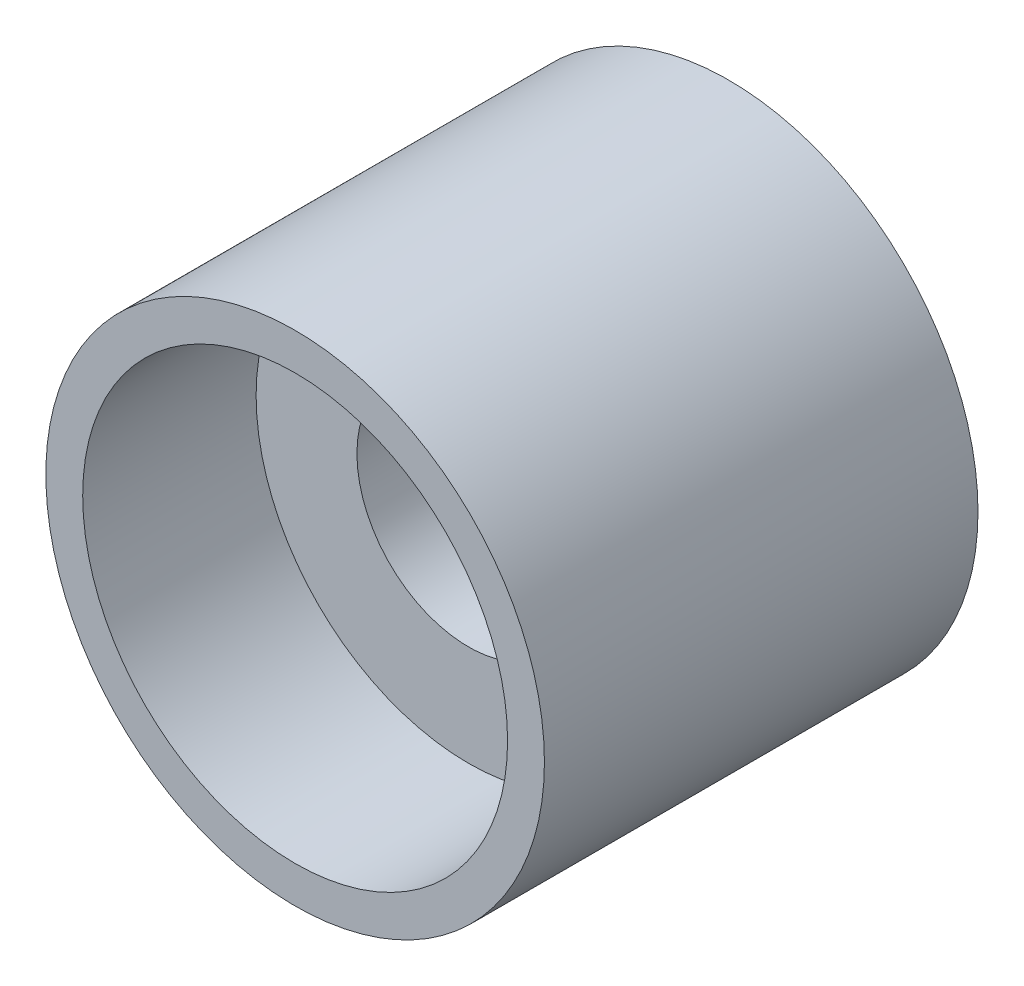
SolidWorks part; units mm, degrees
ref_plane "Front Plane" through (0, 0, 0) normal (0, 0, 1) x (1, 0, 0)
ref_plane "Top Plane" through (0, 0, 0) normal (0, 1, 0) x (1, 0, 0)
ref_plane "Right Plane" through (0, 0, 0) normal (1, 0, 0) x (0, 0, -1)
sketch "Sketch1" plane through (0, 0, 0) normal (0, 0, 1) x (1, 0, 0)
  circle A0 centre (0, 0) radius 11.5
  circle A1 centre (0, 0) radius 5.15
  dimension "D1" = 23
  dimension "D2" = 10.3
extrude "Boss-Extrude1" add sketch "Sketch1" along normal blind 20
sketch "Sketch2" plane through (0, 0, 20) normal (0, 0, 1) x (1, 0, 0)
  circle A0 centre (0, 0) radius 9.8
  circle A1 centre (0, 0) radius 11.5 construction
  dimension "D1" = 1.7
extrude "Cut-Extrude1" cut sketch "Sketch2" against normal blind 8
